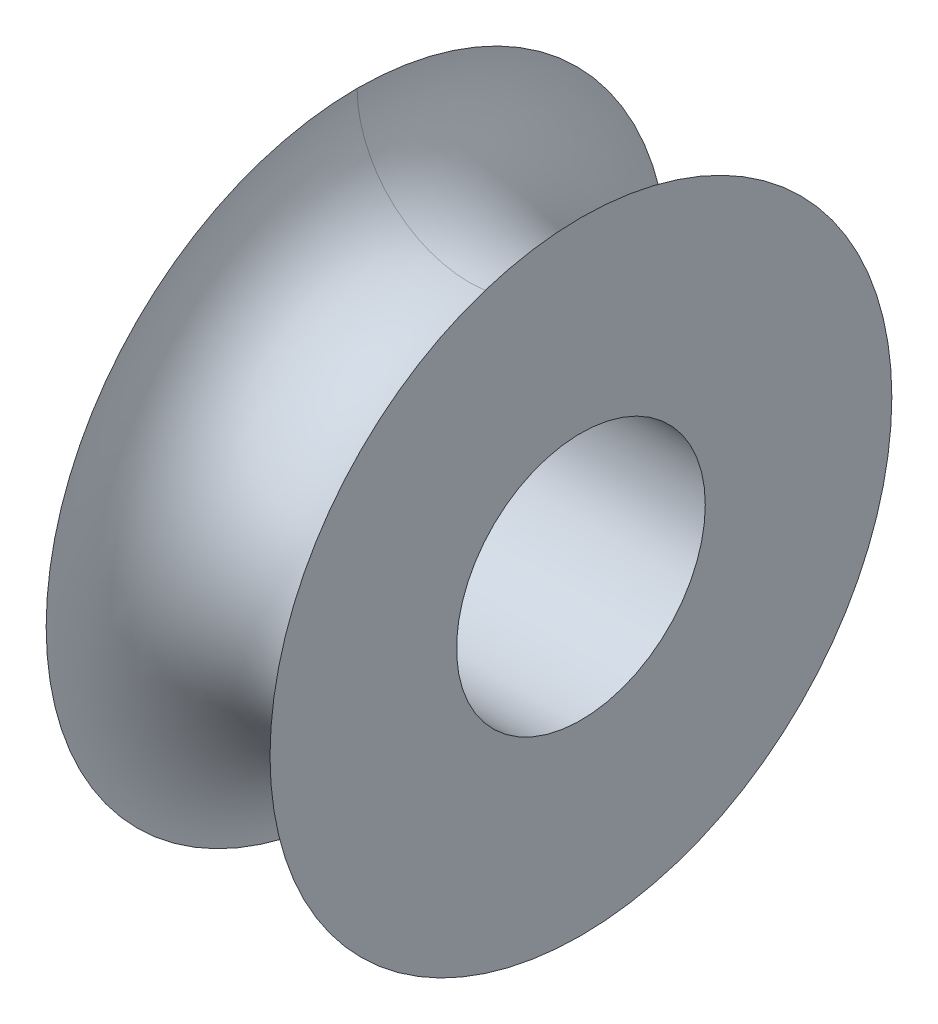
SolidWorks part; units mm, degrees
ref_plane "Front Plane" through (0, 0, 0) normal (0, 0, 1) x (1, 0, 0)
ref_plane "Top Plane" through (0, 0, 0) normal (0, 1, 0) x (1, 0, 0)
ref_plane "Right Plane" through (0, 0, 0) normal (1, 0, 0) x (0, 0, -1)
sketch "Sketch1" plane through (0, 0, 0) normal (1, 0, 0) x (0, 0, -1)
  circle A0 centre (0, 0) radius 2.5
  circle A1 centre (0, 0) radius 1
extrude "Boss-Extrude1" add sketch "Sketch1" along normal blind 1.8
sketch "Sketch18" plane through (0, 0, 0) normal (0, 0, 1) x (1, 0, 0)
  line L0 (-0.1045, 0) -> (2.0599, 0)
sketch "Sketch21" plane through (0, 0, 0) normal (0, 0, 1) x (1, 0, 0)
  line L0 (1.8, 2.5) -> (0, 2.5) construction
  line L1 (0, 2.5) -> (1.8, 2.5)
  arc A0 (0, 2.5) -> (1.8, 2.5) centre (0.9, 2.5) ccw
sweep "Cut-Sweep5" cut profiles "Sketch21" path edge at (0, 0, -2.5)
